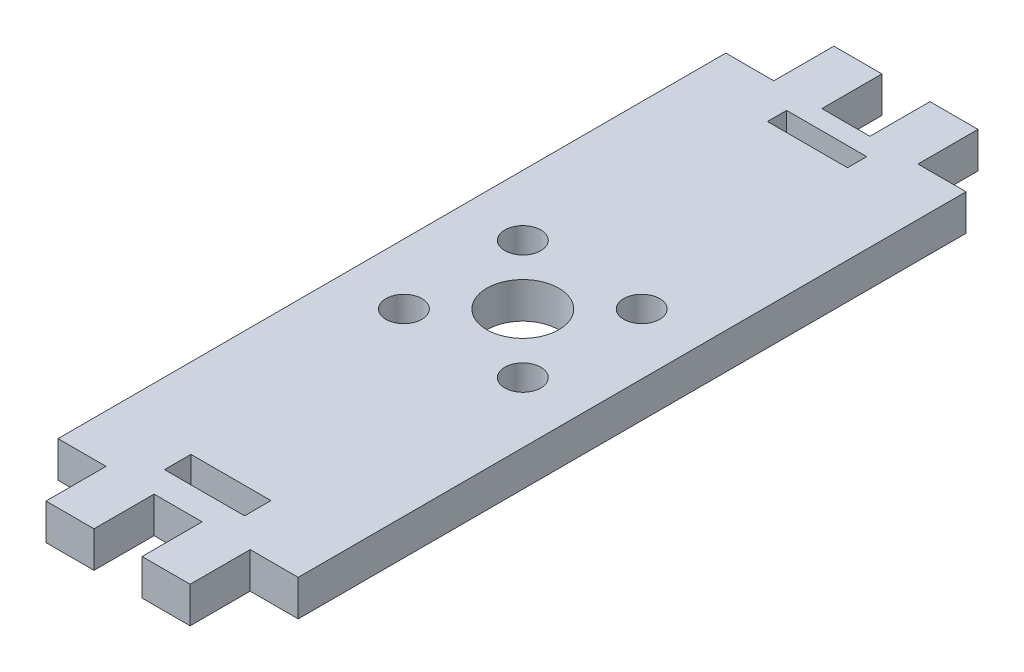
SolidWorks part; units mm, degrees
material "PF"
ref_plane "前视基准面" through (0, 0, 0) normal (0, 0, 1) x (1, 0, 0)
ref_plane "上视基准面" through (0, 0, 0) normal (0, 1, 0) x (1, 0, 0)
ref_plane "右视基准面" through (0, 0, 0) normal (1, 0, 0) x (0, 0, -1)
sketch "草图1" plane through (0, 0, 0) normal (0, 1, 0) x (1, 0, 0)
  line L1 (-20, 0) -> (0, 0)
  line L2 (-20, 0) -> (-20, -55.6)
  line L3 (-20, -55.6) -> (0, -55.6)
  line L4 (0, 0) -> (0, -55.6)
  dimension "D1" = 20
  dimension "D2" = 55.6
extrude "凸台-拉伸1" add sketch "草图1" along normal blind 3
sketch "草图2" plane through (0, 3, 0) normal (0, 1, 0) x (1, 0, 0)
  line L0 (0, -27.8) -> (-20, -27.8) construction
  line L1 (0, -55.6) -> (0, 0) construction
  line L2 (-20, 0) -> (-20, -55.6) construction
  line L3 (-8, 0) -> (-12, 0)
  line L4 (0, 0) -> (-20, 0) construction
  line L5 (-8, 0) -> (-4, 0)
  line L6 (-8, 0) -> (-8, 5)
  line L7 (-4, 0) -> (-4, 5)
  line L8 (-8, 5) -> (-4, 5)
  line L9 (-10, -27.8) -> (-10, 0) construction
  line L10 (-16, 0) -> (-16, 5)
  line L11 (-12, 5) -> (-16, 5)
  line L12 (-12, 0) -> (-12, 5)
  line L13 (-12, 0) -> (-16, 0)
  line L14 (-12, -55.6) -> (-16, -55.6)
  line L15 (-12, -55.6) -> (-12, -60.6)
  line L16 (-12, -60.6) -> (-16, -60.6)
  line L17 (-16, -55.6) -> (-16, -60.6)
  line L18 (-4, -55.6) -> (-4, -60.6)
  line L19 (-8, -60.6) -> (-4, -60.6)
  line L20 (-8, -55.6) -> (-8, -60.6)
  line L21 (-8, -55.6) -> (-4, -55.6)
  point P11 (-10, 0)
  line M13 (-20, -55.6) -> (0, -55.6)
  line M15 (0, 0) -> (-20, 0)
  dimension "D1" = 4
  dimension "D2" = 5
  dimension "D3" = 4
extrude "凸台-拉伸2" add sketch "草图2" against normal blind 3 contours L8 L6 L7 M15 | L3 L12 L11 L10 M15 | L20 L19 L18 M13 | L17 L16 L15 M13
sketch "草图3" plane through (0, 3, 0) normal (0, 1, 0) x (1, 0, 0)
  line L0 (-10, -26.9) -> (-10, -49) construction
  line L3 (-6.6667, -51.2) -> (-6.6667, -53.4)
  line L4 (-10, -26.9) -> (-5.0503, -31.8497)
  line L5 (0, -55.6) -> (-20, -55.6)
  line L6 (0, -55.6) -> (0, -49)
  line L7 (-20, -55.6) -> (-20, -49)
  line L8 (0, -49) -> (-20, -49)
  line L9 (0, 0) -> (-20, 0)
  line L10 (0, 0) -> (0, -4.8)
  line L11 (-20, 0) -> (-20, -4.8)
  line L12 (0, -4.8) -> (-20, -4.8)
  line L13 (-6.6667, -51.2) -> (-13.3333, -51.2)
  line L14 (-6.6667, -53.4) -> (-13.3333, -53.4)
  line L15 (-13.3333, -51.2) -> (-13.3333, -53.4)
  line L16 (-6.6667, -1.6) -> (-6.6667, -3.2)
  line L17 (-6.6667, -1.6) -> (-13.3333, -1.6)
  line L18 (-6.6667, -3.2) -> (-13.3333, -3.2)
  line L19 (-13.3333, -1.6) -> (-13.3333, -3.2)
  line L20 (-8.6264, 0) -> (-8.6264, -1.6) construction
  line L21 (-8.6264, -3.2) -> (-8.6264, -4.8) construction
  line L22 (0, -2.4) -> (-6.6667, -2.4) construction
  line L23 (-13.3333, -2.4) -> (-20, -2.4) construction
  line L24 (-10, -49) -> (-10, -51.2) construction
  line L25 (-10, -53.4) -> (-10, -55.6) construction
  line L26 (-10, -26.9) -> (-10, 0) construction
  circle A0 centre (-10, -26.9) radius 3
  circle A1 centre (-5.0503, -31.8497) radius 1.5
  circle A2 centre (-14.9497, -31.8497) radius 1.5
  circle A3 centre (-14.9497, -21.9503) radius 1.5
  circle A4 centre (-5.0503, -21.9503) radius 1.5
  dimension "D1" = 7
  dimension "D3" = 4.8
  dimension "D4" = 6.6
  dimension "D5" = 26.9
  dimension "D2" = 4
extrude "切除-拉伸1" cut sketch "草图3" against normal blind 10
